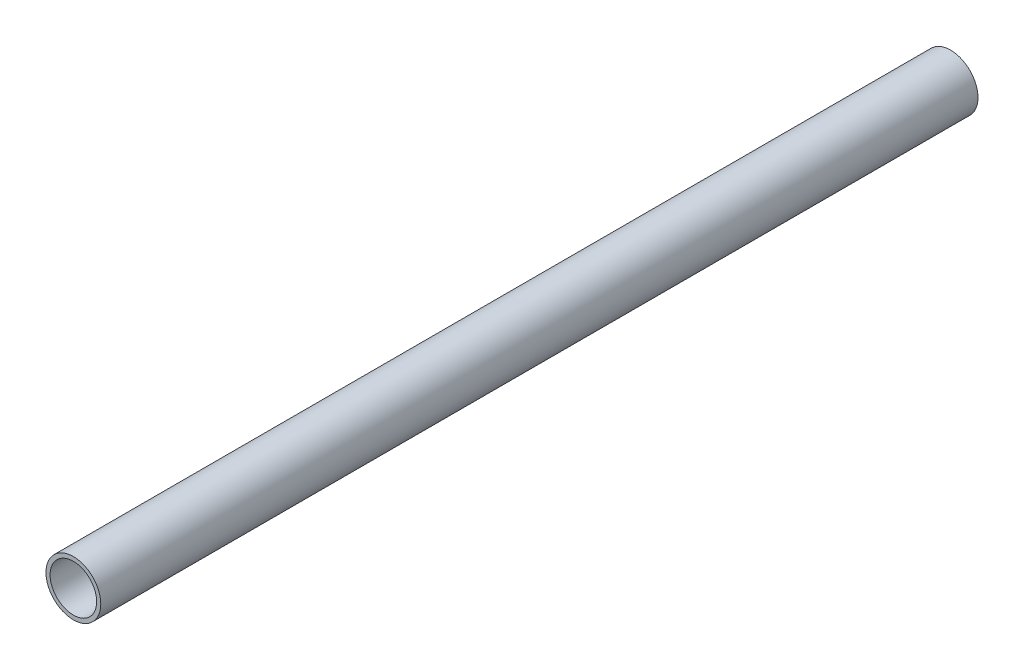
SolidWorks part; units mm, degrees
material "PE Высокой плотности"
ref_plane "Front" through (0, 0, 0) normal (0, 0, 1) x (1, 0, 0)
ref_plane "Top" through (0, 0, 0) normal (0, 1, 0) x (1, 0, 0)
ref_plane "Side" through (0, 0, 0) normal (1, 0, 0) x (0, 0, -1)
sketch "PipeSketch" plane through (0, 0, 0) normal (0, 0, 1) x (1, 0, 0)
  circle A0 centre (0, 0) radius 10
  circle A1 centre (0, 0) radius 8.5
  dimension "OuterDiameter" = 20
  dimension "InnerDiameter" = 17
extrude "Extrusion" add sketch "PipeSketch" along normal blind 320
sketch "FilterSketch" plane through (0, 0, 0) normal (0, 0, 1) x (1, 0, 0)
  circle A0 centre (0, 0) radius 10 construction
  dimension "NominalDiameter" = 20
